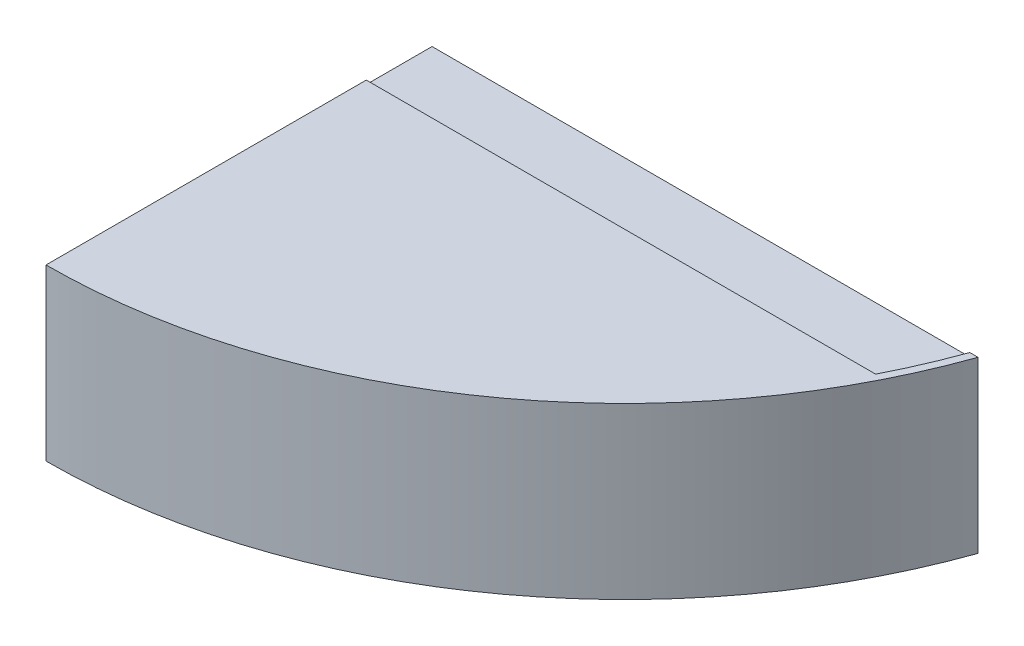
SolidWorks part; units mm, degrees
ref_plane "Front Plane" through (0, 0, 0) normal (0, 0, 1) x (1, 0, 0)
ref_plane "Top Plane" through (0, 0, 0) normal (0, 1, 0) x (1, 0, 0)
ref_plane "Right Plane" through (0, 0, 0) normal (1, 0, 0) x (0, 0, -1)
sketch "Sketch1" plane through (0, 0, 0) normal (0, 1, 0) x (1, 0, 0)
  line L1 (0, -150) -> (0, -50)
  line L3 (0, -50) -> (141.4214, -50)
  arc A0 (0, -150) -> (141.4214, -50) centre (0, 0) ccw
  point P4 (0, -50)
  dimension "D1" = 300
  dimension "D2" = 100
extrude "Boss-Extrude1" add sketch "Sketch1" along normal blind 44
shell "Shell1" thickness 2
sketch "Sketch2" plane through (0, 44, 0) normal (0, 1, 0) x (1, 0, 0)
  line L0 (0, -67.0409) -> (131.9451, -67.0409)
  line L1 (0, -50) -> (0, -150) construction
  line L2 (0, -67.0409) -> (0, -50)
  line L3 (0, -50) -> (139.2982, -50)
  arc A0 (0, -148) -> (139.2982, -50) centre (0, 0) ccw construction
  arc A1 (139.2982, -50) -> (131.9451, -67.0409) centre (0, 0) cw
extrude "Cut-Extrude1" cut sketch "Sketch2" against normal blind 1
